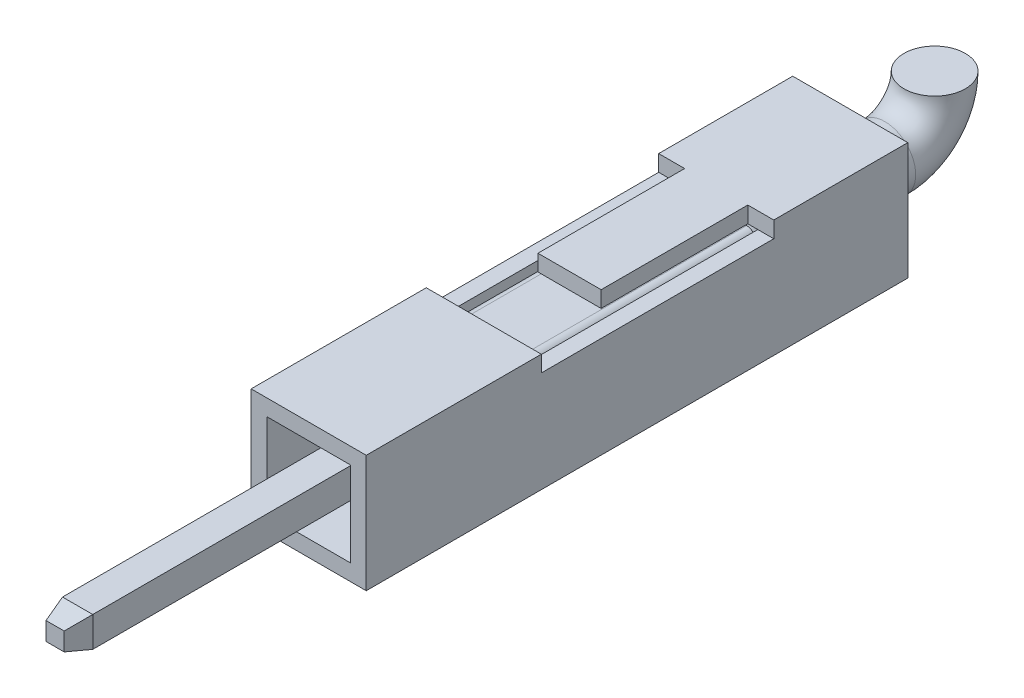
SolidWorks part; units mm, degrees
other "Wire"
ref_plane "Front Plane" through (0, 0, 0) normal (0, 0, 1) x (1, 0, 0)
ref_plane "Top Plane" through (0, 0, 0) normal (0, 1, 0) x (1, 0, 0)
ref_plane "Right Plane" through (0, 0, 0) normal (1, 0, 0) x (0, 0, -1)
sketch "Sketch1" plane through (0, 0, 0) normal (0, 0, 1) x (1, 0, 0)
  line L0 (-0.495, 0.52) -> (0.495, 0.52)
  line L1 (-1.275, 1.3) -> (1.275, 1.3)
  line L2 (-1.275, 1.3) -> (-1.275, -1.3)
  line L3 (-1.275, -1.3) -> (1.275, -1.3)
  line L4 (1.275, 1.3) -> (1.275, -1.3)
  line L5 (-1.275, 1.3) -> (1.275, -1.3) construction
  line L6 (-1.275, -1.3) -> (1.275, 1.3) construction
  line L7 (0.495, 0.52) -> (0.495, -0.52)
  line L8 (-0.495, -0.52) -> (0.495, -0.52)
  line L9 (-0.495, 0.52) -> (-0.495, -0.52)
  point P4 (0, 0)
  dimension "D1" = 2.6
  dimension "D2" = 2.55
  dimension "D3" = 0.78
extrude "Boss-Extrude1" add sketch "Sketch1" along normal blind 12
sketch "Sketch2" plane through (-1.275, 0, 0) normal (-1, 0, 0) x (0, 0, 1)
  line L0 (12, 1.3) -> (0, 1.3) construction
  line L1 (2.97, 1.3) -> (8.12, 1.3)
  line L2 (2.97, 1.3) -> (2.97, 0.94)
  line L3 (2.97, 0.94) -> (8.12, 0.94)
  line L4 (8.12, 1.3) -> (8.12, 0.94)
  line L5 (2.97, 1.3) -> (8.12, 0.94) construction
  line L6 (2.97, 0.94) -> (8.12, 1.3) construction
  line L7 (12, -1.3) -> (0, -1.3) construction
  line L8 (12, 1.3) -> (12, -1.3) construction
  point P4 (5.545, 1.12)
  dimension "D1" = 2.24
  dimension "D2" = 5.15
  dimension "D3" = 3.88
extrude "Cut-Extrude1" cut sketch "Sketch2" against normal up to next
sketch "Sketch3" plane through (0, 0, 0) normal (0, 0, -1) x (-1, 0, 0)
  line L9 (-1.275, 0.94) -> (1.275, 0.94) construction
  line L10 (-0.9219, 0.94) -> (0.9219, 0.94)
  line L11 (-0.9219, 0.94) -> (-0.9219, -0.94)
  line L12 (-0.9219, -0.94) -> (0.9219, -0.94)
  line L13 (0.9219, 0.94) -> (0.9219, -0.94)
  line L14 (-0.9219, 0.94) -> (0.9219, -0.94) construction
  line L19 (-0.9219, -0.94) -> (0.9219, 0.94) construction
  point P7 (0, 0)
extrude "Cut-Extrude2" cut sketch "Sketch3" against normal blind 12
sketch "Sketch4" plane through (0, 1.3, 0) normal (0, 1, 0) x (1, 0, 0)
  line L0 (1.275, -2.97) -> (-1.275, -2.97) construction
  line L1 (0.7, -2.97) -> (-0.7, -2.97)
  line L2 (0.7, -2.97) -> (0.7, -6.22)
  line L3 (0.7, -6.22) -> (-0.7, -6.22)
  line L4 (-0.7, -2.97) -> (-0.7, -6.22)
  line L5 (0.7, -2.97) -> (-0.7, -6.22) construction
  line L6 (0.7, -6.22) -> (-0.7, -2.97) construction
  line L8 (1.275, -8.12) -> (-1.275, -8.12) construction
  point P4 (0, -4.595)
  point P8 (0, -2.97)
  point P13 (0, -2.97)
  dimension "D1" = 1.4
  dimension "D2" = 1.9
extrude "Boss-Extrude2" add sketch "Sketch4" against normal up to surface (0.36 mm away) up to face at (1.0985, 0.94, 5.545)
sketch "Sketch5" plane through (0, 0, 8.12) normal (0, 0, -1) x (-1, 0, 0)
  line L0 (-0.7753, 0.7925) -> (0.7753, 0.7925)
  line L1 (-0.8753, 0.8925) -> (0.8753, 0.8925)
  line L2 (-0.8753, 0.8925) -> (-0.8753, -0.8925)
  line L3 (-0.8753, -0.8925) -> (0.8753, -0.8925)
  line L4 (0.8753, 0.8925) -> (0.8753, -0.8925)
  line L5 (-0.8753, 0.8925) -> (0.8753, -0.8925) construction
  line L6 (-0.8753, -0.8925) -> (0.8753, 0.8925) construction
  line L7 (0.7753, 0.7925) -> (0.7753, -0.7925)
  line L8 (-0.7753, -0.7925) -> (0.7753, -0.7925)
  line L9 (-0.7753, 0.7925) -> (-0.7753, -0.7925)
  point P4 (0, 0)
  dimension "D1" = 0.1
extrude "Boss-Extrude3" add sketch "Sketch5" along normal up to surface (5.15 mm away) separate body up to face at (-0.9744, 1.084, 2.97)
fillet "Fillet1" radius 0.2 4 edges at (0.7753, 0.7925, 5.545) (-0.7753, 0.7925, 5.545) (-0.7753, -0.7925, 5.545) (0.7753, -0.7925, 5.545)
fillet "Fillet2" radius 0.2 4 edges at (0.8753, -0.8925, 5.545) (0.8753, 0.8925, 5.545) (-0.8753, -0.8925, 5.545) (-0.8753, 0.8925, 5.545)
sketch "Sketch6" plane through (0, 0, 0) normal (1, 0, 0) x (0, 0, -1)
  line L0 (1.87, 3.1002) -> (1.87, 1.1002) construction
  line L1 (-2.97, 0) -> (0.7698, 0)
  line L2 (-2.97, 0.5925) -> (-2.97, -0.5925) construction
  line L3 (1.19, 3.1002) -> (1.19, 1.1002) construction
  line L4 (-2.97, 0.68) -> (0.7698, 0.68) construction
  line L5 (-2.97, -0.68) -> (0.7698, -0.68) construction
  line L6 (2.55, 3.1002) -> (2.55, 1.1002) construction
  line L7 (0, -1.3) -> (0, 1.3) construction
  arc A0 (0.7698, 0) -> (1.87, 1.1002) centre (0.7698, 1.1002) ccw
  arc A1 (0.7698, 0.68) -> (1.19, 1.1002) centre (0.7698, 1.1002) ccw construction
  arc A2 (0.7698, -0.68) -> (2.55, 1.1002) centre (0.7698, 1.1002) ccw construction
  dimension "D1" = 0.68
  dimension "D4" = 0.4202
  dimension "D3" = 2.55
  dimension "D5" = 2
  dimension "D2" = 0.68
ref_plane "Plane1" through (0, 0, 2.97) normal (0, 0, -1) x (-1, 0, 0)
sketch "Sketch7" plane through (0, 0, 2.97) normal (0, 0, -1) x (-1, 0, 0)
  circle A0 centre (0, 0) radius 0.68
  dimension "D1" = 1.36
sweep "Sweep2" add profiles "Sketch7" path "Sketch6"
sketch "Sketch8" plane through (0, 0, 8.12) normal (0, 0, 1) x (1, 0, 0)
  line L5 (0.335, 0.335) -> (-0.335, 0.335)
  line L6 (0.335, 0.335) -> (0.335, -0.335)
  line L7 (0.335, -0.335) -> (-0.335, -0.335)
  line L8 (-0.335, 0.335) -> (-0.335, -0.335)
  line L9 (0.335, 0.335) -> (-0.335, -0.335) construction
  line L10 (0.335, -0.335) -> (-0.335, 0.335) construction
  point P4 (0, 0)
  dimension "D1" = 0.67
extrude "Boss-Extrude4" add sketch "Sketch8" along normal offset from surface (9.5 mm away) 5.62 separate body up to face at (0, 0, 12) offset beyond the face yes
chamfer "Chamfer1" distance 0.5 angle 15 4 edges at (-0.335, 0, 17.62) (0, 0.335, 17.62) (0.335, 0, 17.62) (0, -0.335, 17.62)
sketch "Sketch9" plane through (0, 0, 0) normal (1, 0, 0) x (0, 0, -1)
  line L0 (2.55, 1.1002) -> (1.19, 1.1002) construction
  point P0 (1.87, 1.1002)
  point P1 (1.87, 3.0467)
